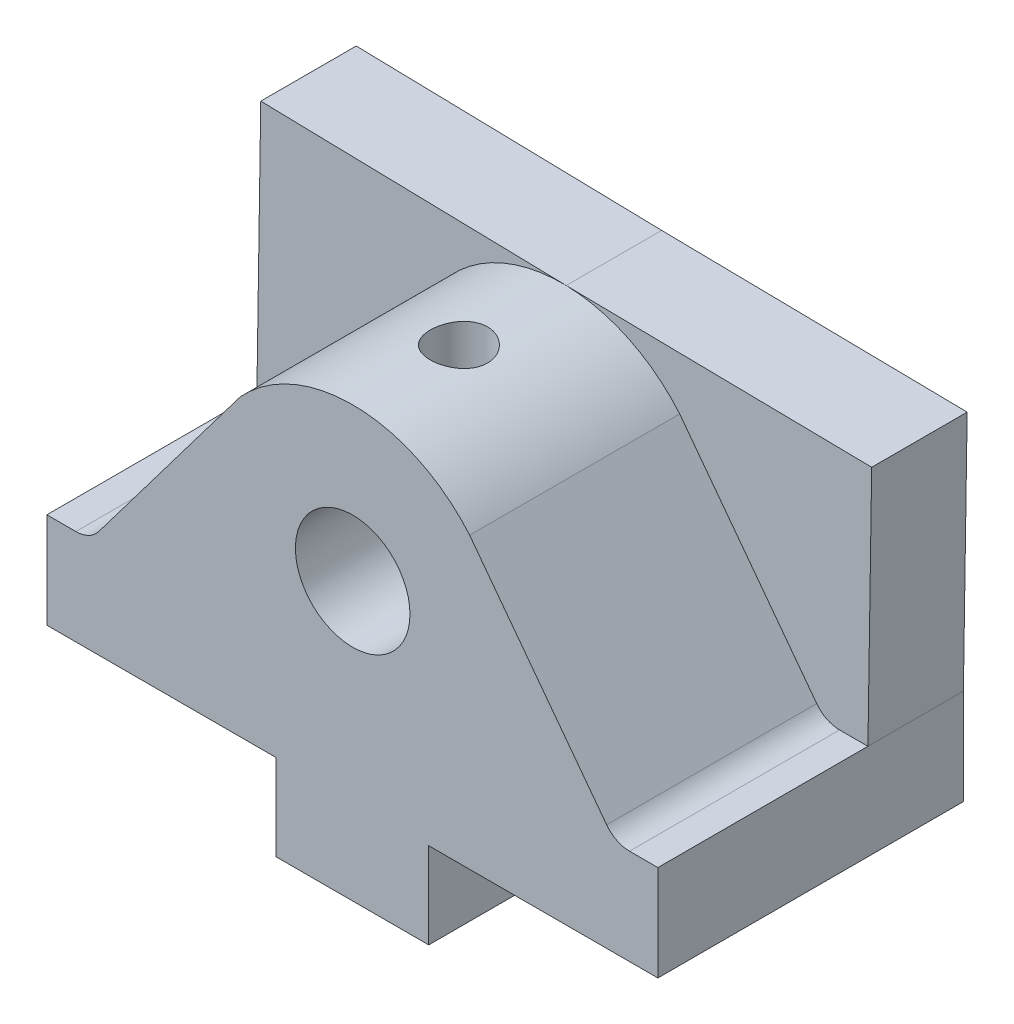
SolidWorks part; units mm, degrees
ref_plane "Front Plane" through (0, 0, 0) normal (0, 0, 1) x (1, 0, 0)
ref_plane "Top Plane" through (0, 0, 0) normal (0, 1, 0) x (1, 0, 0)
ref_plane "Right Plane" through (0, 0, 0) normal (1, 0, 0) x (0, 0, -1)
sketch "Sketch1" plane through (0, 0, 0) normal (0, 0, 1) x (1, 0, 0)
  line L4 (0, 16) -> (31.967, 16)
  line L5 (0, 16) -> (-32.033, 16)
  line L11 (-32.033, 16) -> (-32.033, -20.0165)
  line L12 (31.967, 16) -> (31.967, -20.0165)
  line L14 (-0.033, -29.0165) -> (7.967, -29.0165)
  line L15 (7.967, -29.0165) -> (7.967, -20.0165)
  line L16 (7.967, -20.0165) -> (31.967, -20.0165)
  line L17 (-0.033, -29.0165) -> (-8.033, -29.0165)
  line L18 (-8.033, -29.0165) -> (-8.033, -20.0165)
  line L19 (-8.033, -20.0165) -> (-32.033, -20.0165)
  line L20 (31.967, -20.0165) -> (27.5, -20.0165)
  line L22 (28.9982, -10) -> (31.967, -10)
  line L23 (-32.033, -20.0165) -> (-27.5, -20.0165)
  line L25 (-28.9942, -10) -> (-32.033, -10)
  line L26 (-26.5998, -8.8075) -> (-11.7685, 10.8398)
  line L27 (26.5999, -8.8023) -> (12.2506, 10.2919)
  circle A0 centre (0, 0) radius 6
  arc A2 (13.2933, 8.9044) -> (-13.6497, 8.3478) centre (0, 0) ccw
  arc A3 (26.5999, -8.8023) -> (28.9982, -10) centre (28.9982, -7) ccw
  arc A4 (-28.9942, -10) -> (-26.5998, -8.8075) centre (-28.9942, -7) ccw
  dimension "D1" = 12
  dimension "D2" = 16
  dimension "D3" = 3
  dimension "D4" = 3
extrude "Boss-Extrude1" add sketch "Sketch1" against normal blind 22 contours A4 L25 L11 L19 L18 L17 L14 L15 L16 L12 L22 A3 L27 A2 L26 A0
sketch "Sketch3" plane through (0, 0, 0) normal (0, 1, 0) x (1, 0, 0)
  circle A0 centre (0, 11.1252) radius 3
  dimension "D1" = 6
extrude "Cut-Extrude2" cut sketch "Sketch3" along normal blind 22
sketch "Sketch4" plane through (0, 0, -22) normal (0, 0, -1) x (-1, 0, 0)
  line L0 (-0.3649, 15.9958) -> (31.6268, 16.7256)
  line L1 (31.6268, 16.7256) -> (32.033, -10)
  line L2 (-0.3649, 15.9958) -> (-32.3612, 15.5095)
  line L3 (-32.3612, 15.5095) -> (-31.967, -10)
  line L15 (26.5998, -8.8075) -> (11.7685, 10.8398)
  line L16 (-12.2506, 10.2919) -> (-26.5999, -8.8023)
  line L17 (-28.9982, -10) -> (-31.967, -10)
  line L18 (-31.967, -10) -> (-31.967, -20.0165)
  line L19 (-31.967, -20.0165) -> (-7.967, -20.0165)
  line L20 (-7.967, -20.0165) -> (-7.967, -29.0165)
  line L21 (-7.967, -29.0165) -> (8.033, -29.0165)
  line L22 (8.033, -29.0165) -> (8.033, -20.0165)
  line L23 (8.033, -20.0165) -> (32.033, -20.0165)
  line L24 (32.033, -20.0165) -> (32.033, -10)
  line L25 (32.033, -10) -> (28.9942, -10)
  line L26 (26.5998, -8.8075) -> (11.7685, 10.8398)
  line L27 (-12.2506, 10.2919) -> (-26.5999, -8.8023)
  line L28 (-28.9982, -10) -> (-31.967, -10)
  line L36 (32.033, -10) -> (28.9942, -10)
  arc A0 (11.7685, 10.8398) -> (-12.2506, 10.2919) centre (0, 0) ccw construction
  arc A4 (26.5998, -8.8075) -> (28.9942, -10) centre (28.9942, -7) ccw
  arc A5 (11.7685, 10.8398) -> (-12.2506, 10.2919) centre (0, 0) ccw
  arc A6 (-28.9982, -10) -> (-26.5999, -8.8023) centre (-28.9982, -7) ccw
  arc A7 (26.5998, -8.8075) -> (28.9942, -10) centre (28.9942, -7) ccw
  arc A8 (11.7685, 10.8398) -> (-12.2506, 10.2919) centre (0, 0) ccw
  arc A9 (-28.9982, -10) -> (-26.5999, -8.8023) centre (-28.9982, -7) ccw
  arc M15 (28.9942, -10) -> (26.5998, -8.8075) centre (28.9942, -7) cw
  line M16 (26.5998, -8.8075) -> (11.7685, 10.8398)
  arc M17 (11.7685, 10.8398) -> (-12.2506, 10.2919) centre (0, 0) ccw
  line M18 (-12.2506, 10.2919) -> (-26.5999, -8.8023)
  arc M19 (-26.5999, -8.8023) -> (-28.9982, -10) centre (-28.9982, -7) cw
  line M20 (-28.9982, -10) -> (-31.967, -10)
  line M21 (-31.967, -10) -> (-31.967, -20.0165)
  line M22 (-31.967, -20.0165) -> (-7.967, -20.0165)
  line M23 (-7.967, -20.0165) -> (-7.967, -29.0165)
  line M24 (-7.967, -29.0165) -> (8.033, -29.0165)
  line M25 (8.033, -29.0165) -> (8.033, -20.0165)
  line M26 (8.033, -20.0165) -> (32.033, -20.0165)
  line M27 (32.033, -20.0165) -> (32.033, -10)
  line M28 (32.033, -10) -> (28.9942, -10)
  circle M29 centre (0, 0) radius 6
  dimension "D1" = 0
extrude "Boss-Extrude2" add sketch "Sketch4" along normal blind 10 contours L2 L3 M20 M19 M18 M17 | L1 L0 M17 M16 M15 M28 | M28 M15 M16 M17 M18 M19 M20 M21 M22 M23 M24 M25 M26 M27 M29
sketch "Sketch5" plane through (0, -29.0165, 0) normal (0, -1, 0) x (1, 0, 0)
  circle A0 centre (-0.5794, -15.4233) radius 3
extrude "Cut-Extrude3" cut sketch "Sketch5" against normal blind 16
